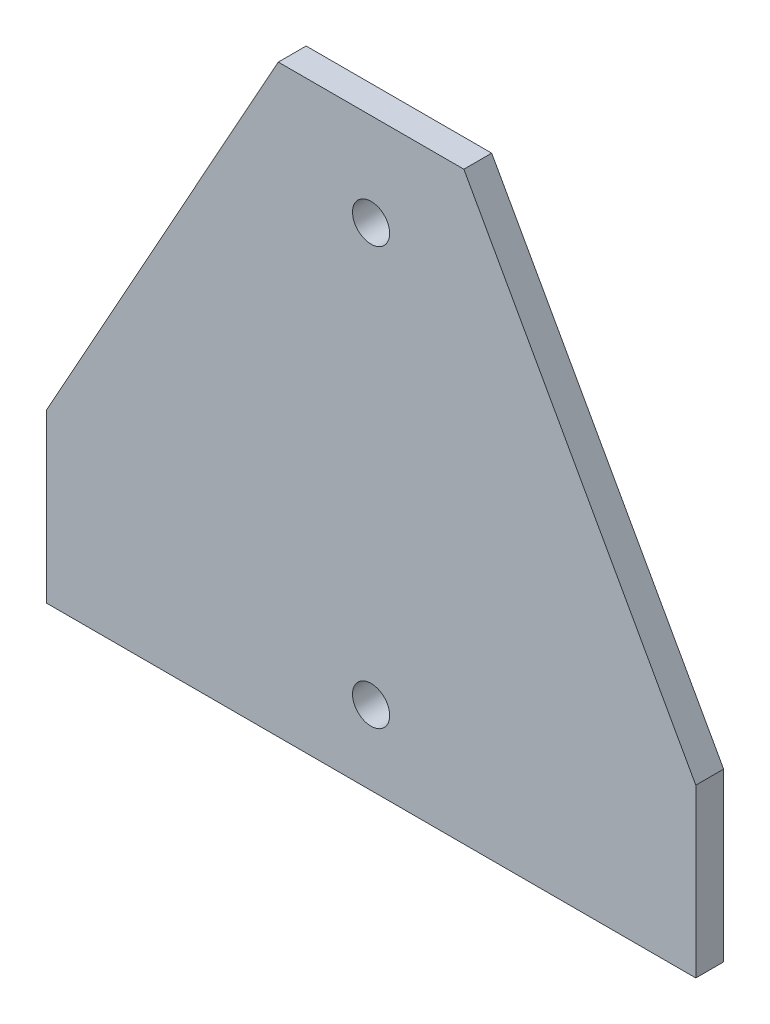
SolidWorks part; units mm, degrees
ref_plane "Ön Düzlem" through (0, 0, 0) normal (0, 0, 1) x (1, 0, 0)
ref_plane "Üst Düzlem" through (0, 0, 0) normal (0, 1, 0) x (1, 0, 0)
ref_plane "Sağ Düzlem" through (0, 0, 0) normal (1, 0, 0) x (0, 0, -1)
sketch "Çizim1" plane through (0, 0, 0) normal (0, 0, 1) x (1, 0, 0)
  line L0 (35, 18) -> (35, 63) construction
  line L1 (0, 0) -> (70, 0)
  line L2 (0, 0) -> (0, 18)
  line L3 (0, 18) -> (70, 18)
  line L4 (70, 0) -> (70, 18)
  line L5 (0, 18) -> (25, 63)
  line L6 (25, 63) -> (45, 63)
  line L7 (45, 63) -> (70, 18)
  line L8 (35, 18) -> (35, 0) construction
  circle A0 centre (35, 53) radius 2
  circle A1 centre (35, 8) radius 2
  dimension "D5" = 4
  dimension "D7" = 4
  dimension "D1" = 18
  dimension "D2" = 70
  dimension "D3" = 45
  dimension "D4" = 20
  dimension "D6" = 10
  dimension "D8" = 10
extrude "Yükseklik-Ekstrüzyon1" add sketch "Çizim1" along normal blind 3 contours L7 L6 L5 L3 A0 | L1 L4 L3 L2 A1
